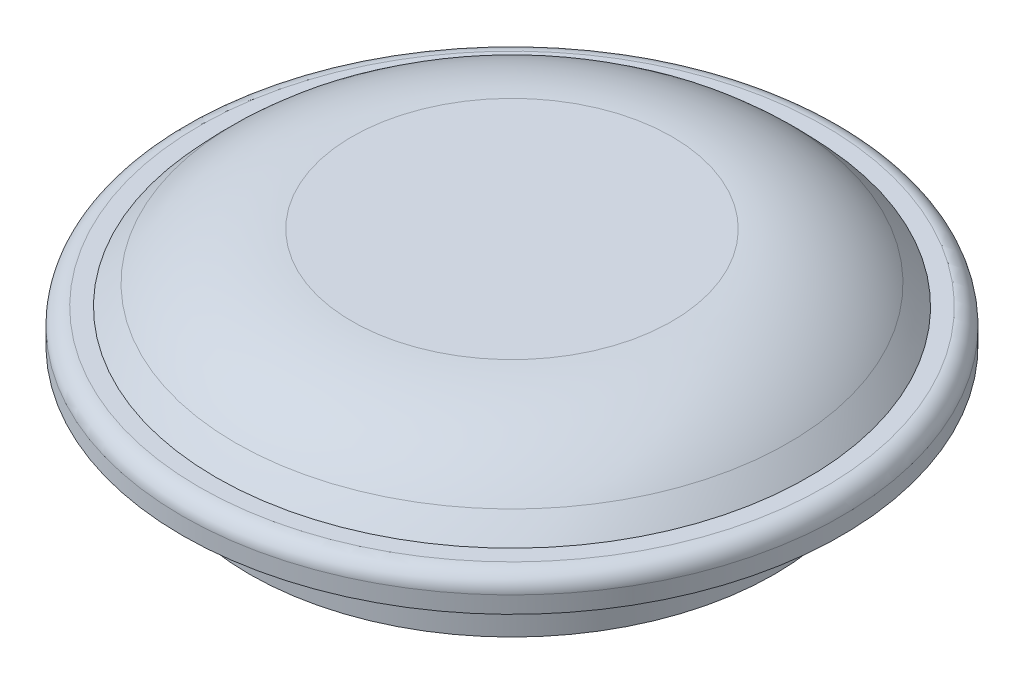
SolidWorks part; units mm, degrees
ref_plane "Front Plane" through (0, 0, 0) normal (0, 0, 1) x (1, 0, 0)
ref_plane "Top Plane" through (0, 0, 0) normal (0, 1, 0) x (1, 0, 0)
ref_plane "Right Plane" through (0, 0, 0) normal (1, 0, 0) x (0, 0, -1)
sketch "Sketch1" plane through (0, 0, 0) normal (0, 1, 0) x (1, 0, 0)
  circle A0 centre (0, 0) radius 9.9267
  circle A2 centre (0, 0) radius 10.1267 construction
  dimension "D1" = 0.2
extrude "Boss-Extrude1" add sketch "Sketch1" along normal blind 2.54
sketch "Sketch2" plane through (0, 2.54, 0) normal (0, 1, 0) x (1, 0, 0)
  circle A0 centre (0, 0) radius 12.4667
  circle A1 centre (0, 0) radius 9.9267 construction
  dimension "D1" = 2.54
extrude "Boss-Extrude2" add sketch "Sketch2" along normal blind 1.27
sketch "Sketch3" plane through (0, 0, 0) normal (0, 0, 1) x (1, 0, 0)
  line L0 (12.4667, 3.81) -> (-12.4667, 3.81) construction
  line L1 (-14.4871, 8.8321) -> (13.9911, 8.8321) construction
  line L2 (0, 8.8318) -> (0, 3.81)
  line L3 (0, 3.81) -> (-11.1967, 3.81)
  arc A0 (-11.1967, 3.81) -> (0, 8.8318) centre (0.099, -6.3821) cw
  dimension "D1" = 1.27
revolve "Revolve1" add sketch "Sketch3" angle 360 about L2
fillet "Fillet1" radius 0.635 1 edges at (0, 3.81, 12.4667)
sketch "Sketch4" plane through (0, 0, 0) normal (0, 0, 1) x (1, 0, 0)
  line L0 (11.8317, 3.81) -> (-11.8317, 3.81) construction
  line L1 (-14.9346, 6.35) -> (12.3131, 6.35)
  line L2 (-14.9346, 6.35) -> (-14.9346, 12.7)
  line L3 (-14.9346, 12.7) -> (12.3131, 12.7)
  line L4 (12.3131, 6.35) -> (12.3131, 12.7)
  dimension "D1" = 2.54
  dimension "D2" = 6.35
extrude "Cut-Extrude1" cut sketch "Sketch4" against normal through all both and the other way through all
fillet "Fillet2" radius 6.35 1 edges at (0, 6.35, -8.2296)
